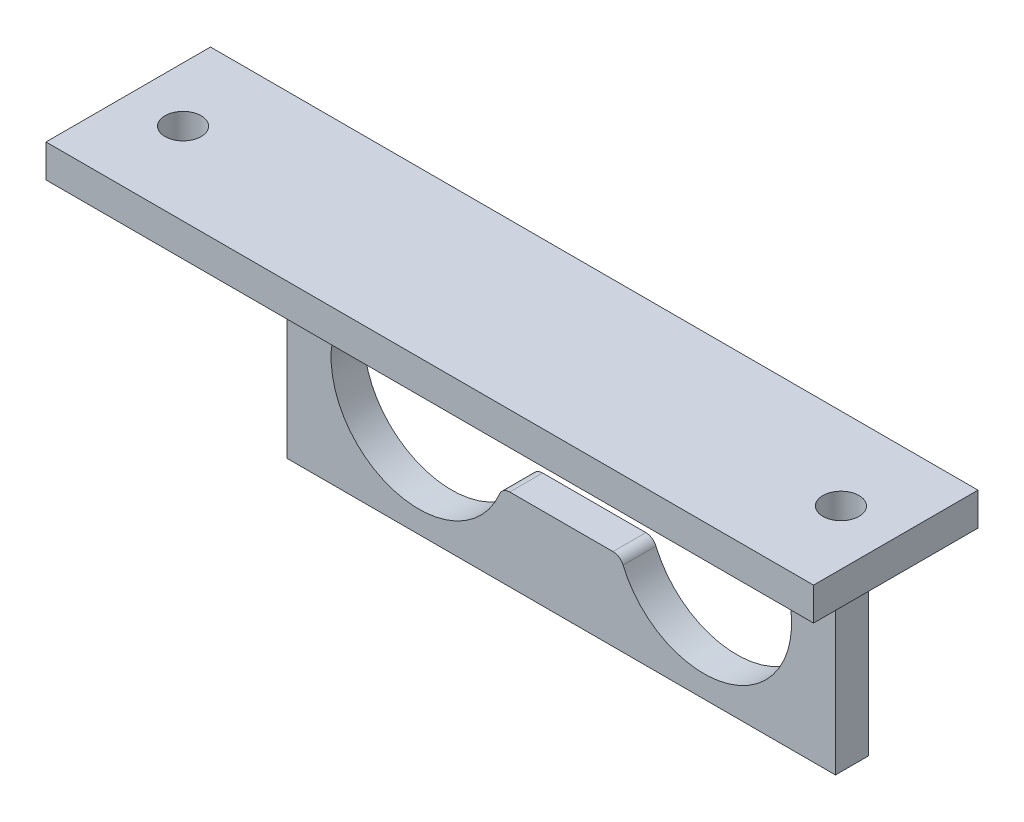
SolidWorks part; units mm, degrees
ref_plane "前视基准面" through (0, 0, 0) normal (0, 0, 1) x (1, 0, 0)
ref_plane "上视基准面" through (0, 0, 0) normal (0, 1, 0) x (1, 0, 0)
ref_plane "右视基准面" through (0, 0, 0) normal (1, 0, 0) x (0, 0, -1)
sketch "草图1" plane through (0, 0, 0) normal (0, 0, 1) x (1, 0, 0)
  line L1 (25, -10) -> (-25, -10)
  line L2 (25, -10) -> (25, 10)
  line L3 (25, 10) -> (-25, 10)
  line L4 (-25, -10) -> (-25, 10)
  line L5 (25, -10) -> (-25, 10) construction
  line L6 (25, 10) -> (-25, -10) construction
  line L8 (-4.7084, 2.5) -> (4.7084, 2.5)
  line L9 (4.7084, -2.5) -> (-4.7084, -2.5)
  line L10 (3.25, 7.25) -> (-3.25, 7.25) construction
  line L11 (3.25, 5.5) -> (-3.25, 5.5)
  line L12 (3.25, 9) -> (-3.25, 9)
  arc A7 (5.6297, -3.1111) -> (5.6297, 3.1111) centre (13, 0) ccw
  arc A8 (-5.6297, 3.1111) -> (-5.6297, -3.1111) centre (-13, 0) ccw
  arc A9 (4.7084, -2.5) -> (5.6297, -3.1111) centre (4.7084, -3.5) cw
  arc A10 (4.7084, 2.5) -> (5.6297, 3.1111) centre (4.7084, 3.5) ccw
  arc A11 (-4.7084, -2.5) -> (-5.6297, -3.1111) centre (-4.7084, -3.5) ccw
  arc A12 (-4.7084, 2.5) -> (-5.6297, 3.1111) centre (-4.7084, 3.5) cw
  arc A13 (3.25, 5.5) -> (3.25, 9) centre (3.25, 7.25) ccw
  arc A14 (-3.25, 9) -> (-3.25, 5.5) centre (-3.25, 7.25) ccw
  point P0 (0, 0)
  point P22 (0, 7.25)
  dimension "D3" = 1
  dimension "D4" = 8
  dimension "D5" = 8
  dimension "D6" = 2.5
  dimension "D8" = 13
  dimension "D9" = 13
  dimension "D12" = 1.75
  dimension "D1" = 20
  dimension "D2" = 50
  dimension "D7" = 2.5
  dimension "D10" = 7.25
  dimension "D11" = 6.5
  dimension "D13" = 3.25
extrude "凸台-拉伸1" add sketch "草图1" along normal blind 3
sketch "草图2" plane through (0, 10, 0) normal (0, 1, 0) x (1, 0, 0)
  line L1 (-25, 0) -> (25, 0)
  line L2 (-25, 0) -> (-25, -15)
  line L3 (-25, -15) -> (25, -15)
  line L4 (25, 0) -> (25, -15)
  dimension "D1" = 15
extrude "凸台-拉伸2" add sketch "草图2" along normal blind 6
sketch "草图5" plane through (0, 10, 0) normal (0, -1, 0) x (1, 0, 0)
  line L1 (25, 3) -> (-25, 3)
  line L2 (25, 3) -> (25, 15)
  line L3 (25, 15) -> (-25, 15)
  line L4 (-25, 3) -> (-25, 15)
extrude "切除-拉伸2" cut sketch "草图5" against normal blind 3
sketch "草图6" plane through (0, 16, 0) normal (0, 1, 0) x (1, 0, 0)
  line L1 (25, -15) -> (35, -15)
  line L2 (25, -15) -> (25, 0)
  line L3 (25, 0) -> (35, 0)
  line L4 (35, -15) -> (35, 0)
  line L5 (-25, -15) -> (-35, -15)
  line L6 (-25, -15) -> (-25, 0)
  line L7 (-25, 0) -> (-35, 0)
  line L8 (-35, -15) -> (-35, 0)
  circle A0 centre (30, -7.5) radius 1.65
  circle A1 centre (-30, -7.5) radius 1.65
  dimension "D5" = 3.3
  dimension "D6" = 3.3
  dimension "D1" = 15
  dimension "D2" = 10
  dimension "D3" = 10
  dimension "D4" = 15
extrude "凸台-拉伸3" add sketch "草图6" against normal blind 3
fillet "圆角1" radius 1 2 edges at (25, 13, 1.5) (-25, 13, 1.5)
